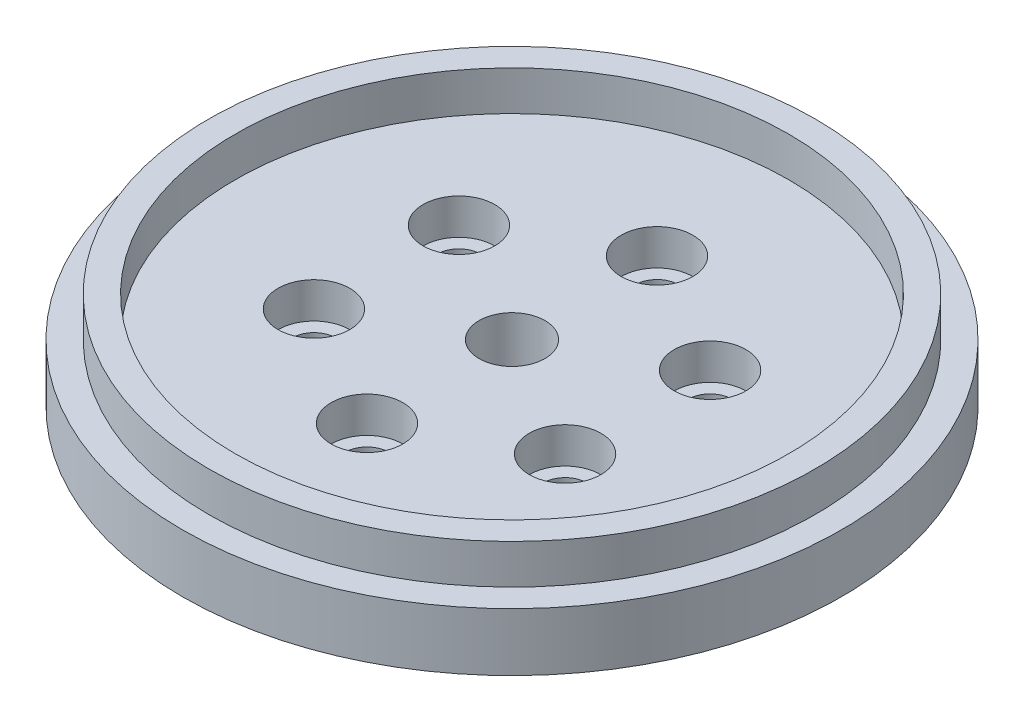
SolidWorks part; units mm, degrees
ref_plane "Front Plane" through (0, 0, 0) normal (0, 0, 1) x (1, 0, 0)
ref_plane "Top Plane" through (0, 0, 0) normal (0, 1, 0) x (1, 0, 0)
ref_plane "Right Plane" through (0, 0, 0) normal (1, 0, 0) x (0, 0, -1)
sketch "Sketch1" plane through (0, 0, 0) normal (0, 1, 0) x (1, 0, 0)
  circle A0 centre (0, 0) radius 13.97 construction
  circle A8 centre (0, 0) radius 31.75
  circle A10 centre (0, 13.97) radius 3.4544 construction
  circle A11 centre (12.0984, 6.985) radius 3.4544 construction
  circle A12 centre (12.0984, -6.985) radius 3.4544 construction
  circle A13 centre (0, -13.97) radius 3.4544 construction
  circle A14 centre (-12.0984, -6.985) radius 3.4544 construction
  circle A15 centre (-12.0984, 6.985) radius 3.4544 construction
  point P17 (0, 0)
  dimension "D1" = 27.94
  dimension "D2" = 6.9088
  dimension "D4" = 63.5
  dimension "D3" = 6
extrude "Boss-Extrude1" add sketch "Sketch1" against normal blind 5.588
sketch "Sketch2" plane through (0, -5.588, 0) normal (0, -1, 0) x (1, 0, 0)
  line L3 (-31.75, 0) -> (31.75, 0) construction
  circle A0 centre (0, 0) radius 13.97 construction
  circle A1 centre (0, 13.97) radius 2.0955
  circle A2 centre (12.0984, 6.985) radius 2.0955
  circle A3 centre (12.0984, -6.985) radius 2.0955
  circle A4 centre (0, -13.97) radius 2.0955
  circle A5 centre (-12.0984, -6.985) radius 2.0955
  circle A12 centre (0, 0) radius 31.75 construction
  circle A13 centre (-12.0984, 6.985) radius 2.0955
  circle A15 centre (0, 0) radius 13.97 construction
  dimension "D1" = 4.191
  dimension "D2" = 6
extrude "Cut-Extrude1" cut sketch "Sketch2" against normal blind 7.62
sketch "Sketch5" plane through (0, 0, 0) normal (0, 1, 0) x (1, 0, 0)
  circle A0 centre (0, 0) radius 13.97 construction
  circle A1 centre (0, 0) radius 13.97 construction
  circle A2 centre (12.0984, -6.985) radius 3.4544
  circle A3 centre (12.0984, -6.985) radius 3.4544 construction
  circle A4 centre (0, -13.97) radius 3.4544
  circle A5 centre (-12.0984, -6.985) radius 3.4544
  circle A6 centre (-12.0984, 6.985) radius 3.4544
  circle A7 centre (0, 13.97) radius 3.4544
  circle A8 centre (12.0984, 6.985) radius 3.4544
  dimension "D1" = 6
extrude "Cut-Extrude2" cut sketch "Sketch5" against normal blind 3.4544
sketch "Sketch6" plane through (0, -5.588, 0) normal (0, -1, 0) x (1, 0, 0)
  circle A0 centre (0, 0) radius 3.175
  dimension "D1" = 6.35
extrude "Cut-Extrude3" cut sketch "Sketch6" against normal through all
sketch "Sketch9" plane through (0, 0, 0) normal (0, 1, 0) x (1, 0, 0)
  circle A0 centre (0, 0) radius 27.94 construction
  circle A1 centre (0, 0) radius 27.94 construction
  circle A2 centre (0, 0) radius 29.21
  circle A3 centre (0, 0) radius 26.67
  dimension "D1" = 1.27
  dimension "D2" = 1.27
extrude "Boss-Extrude3" add sketch "Sketch9" along normal blind 3.81
